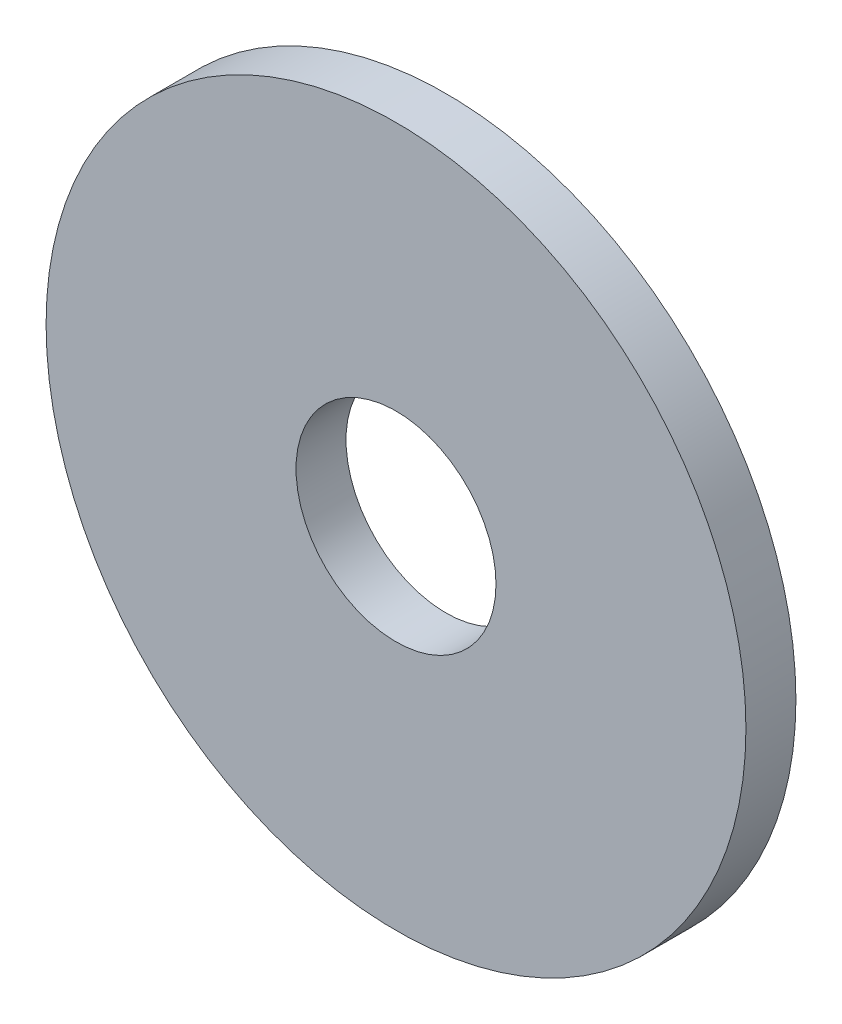
SolidWorks part; units mm, degrees
ref_plane "Front Plane" through (0, 0, 0) normal (0, 0, 1) x (1, 0, 0)
ref_plane "Top Plane" through (0, 0, 0) normal (0, 1, 0) x (1, 0, 0)
ref_plane "Right Plane" through (0, 0, 0) normal (1, 0, 0) x (0, 0, -1)
sketch "Sketch1" plane through (0, 0, 0) normal (0, 0, 1) x (1, 0, 0)
  circle A0 centre (0, 0) radius 7
  circle A1 centre (0, 0) radius 2
  dimension "D1" = 14
  dimension "D2" = 4
extrude "Boss-Extrude1" add sketch "Sketch1" along normal blind 1
